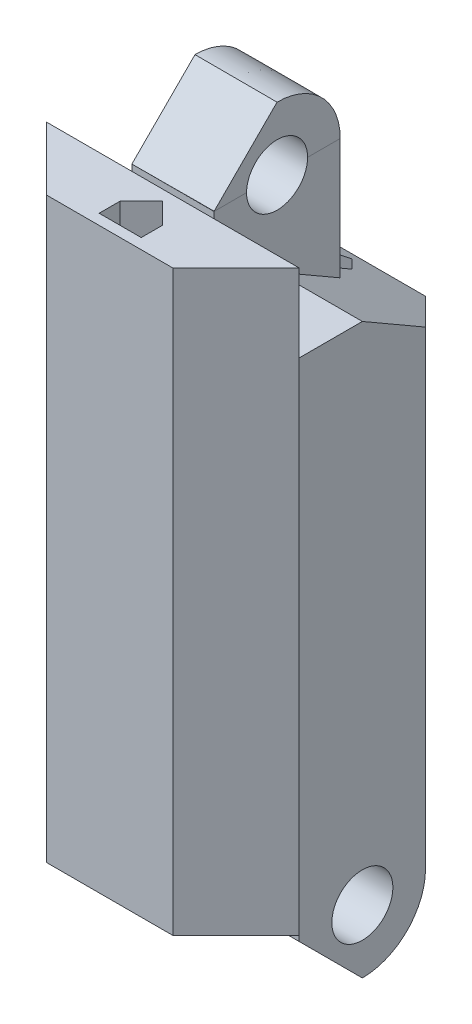
SolidWorks part; units mm, degrees
ref_plane "Front Plane" through (0, 0, 0) normal (0, 0, 1) x (1, 0, 0)
ref_plane "Top Plane" through (0, 0, 0) normal (0, 1, 0) x (1, 0, 0)
ref_plane "Right Plane" through (0, 0, 0) normal (1, 0, 0) x (0, 0, -1)
sketch "Sketch2" plane through (0, 0, 0) normal (0, 1, 0) x (1, 0, 0)
  line L0 (-3, 6) -> (3, 6)
  line L1 (3, 6) -> (6, 3)
  line L2 (6, 3) -> (6, -3)
  line L3 (6, -3) -> (3, -6)
  line L4 (3, -6) -> (-3, -6)
  line L5 (-3, -6) -> (-6, -3)
  line L6 (-6, -3) -> (-6, 3)
  line L7 (-6, 3) -> (-3, 6)
  point P2 (0, -6)
  point P9 (0, 6)
  point P12 (-6, 0)
  point P13 (6, 0)
  dimension "D1" = 12
  dimension "D2" = 12
  dimension "D3" = 6
  dimension "D4" = 6
  dimension "D5" = 6
extrude "Boss-Extrude1" add sketch "Sketch2" along normal mid plane 20 contours L7 L0 L1 L2 L3 L4 L5 L6
sketch "Sketch5" plane through (0, 0, 0) normal (1, 0, 0) x (0, 0, -1)
  line L1 (3, 10) -> (-3, 10) construction
  line L2 (0, 10) -> (6, 6.5359)
  line L3 (6, 10) -> (6, -10) construction
  line L4 (6, 6.5359) -> (6, 10)
  line L5 (6, 10) -> (0, 10)
  dimension "D1" = 30
extrude "Cut-Extrude2" cut sketch "Sketch5" against normal through all both and the other way through all
mirror "Mirror3" about plane through (0, 0, 0) normal (0, 1, 0) of "Cut-Extrude2"
sketch "Sketch6" plane through (0, -10, 0) normal (0, -1, 0) x (1, 0, 0)
  line L1 (-6, 3) -> (-2.1, 3)
  line L2 (-6, 3) -> (-6, -3)
  line L3 (-6, -3) -> (-2.1, -3)
  line L4 (-2.1, 3) -> (-2.1, -3)
  dimension "D1" = 3.9
extrude "Boss-Extrude3" add sketch "Sketch6" along normal mid plane 8
sketch "Sketch7" plane through (0, -14, 0) normal (0, -1, 0) x (1, 0, 0)
  line L0 (-6, 3) -> (-6, -3) construction
  line L1 (-6, 0) -> (-2.1, 0)
  line L2 (-6, 0) -> (-6, 3)
  line L3 (-6, 3) -> (-2.1, 3)
  line L4 (-2.1, 0) -> (-2.1, 3)
revolve "Revolve1" add sketch "Sketch7" angle 180 about L1
sketch "Sketch8" plane through (-6, 0, 0) normal (-1, 0, 0) x (0, 0, 1)
  line L0 (-3, -14) -> (3, -14) construction
sketch "Sketch9" plane through (-6, 0, 0) normal (-1, 0, 0) x (0, 0, 1)
  line L0 (-3, -14) -> (3, -14) construction
  circle A0 centre (0, -14) radius 1.45
  dimension "D1" = 2.9
extrude "Cut-Extrude3" cut sketch "Sketch9" against normal mid plane 10
mirror "Mirror5" about plane through (0, 0, 0) normal (1, 0, 0) of "Revolve1", "Boss-Extrude3", "Cut-Extrude3"
sketch "Sketch10" plane through (0, 10, 0) normal (0, 1, 0) x (1, 0, 0)
  line L0 (-6, -3) -> (6, -3) construction
  line L1 (-1.95, -3) -> (1.95, -3)
  line L2 (-1.95, -3) -> (-1.95, 3)
  line L3 (-1.95, 3) -> (1.95, 3)
  line L4 (1.95, -3) -> (1.95, 3)
  line L5 (-1.95, -3) -> (1.95, 3) construction
  line L6 (-1.95, 3) -> (1.95, -3) construction
  point P6 (0, 0)
  dimension "D1" = 3.9
extrude "Boss-Extrude4" add sketch "Sketch10" along normal mid plane 8
sketch "Sketch12" plane through (0, 14, 0) normal (0, 1, 0) x (1, 0, 0)
  line L0 (-1.95, 3) -> (-1.95, 0)
  line L3 (-1.95, 3) -> (1.95, 3)
  line L4 (1.95, 0.0037) -> (1.95, 3)
  line L5 (-1.95, 3) -> (-1.95, -3) construction
  line L6 (-1.95, 0) -> (1.95, 0.0037)
revolve "Revolve2" add sketch "Sketch12" angle 180 about L6
sketch "Sketch13" plane through (-1.95, 0, 0) normal (-1, 0, 0) x (0, 0, 1)
  line L0 (-3, 14) -> (3, 14) construction
  line L1 (0, 14) -> (3, 14) construction
sketch "Sketch14" plane through (-1.95, 0, 0) normal (-1, 0, 0) x (0, 0, 1)
  line L0 (-3, 14) -> (3, 14) construction
  circle A0 centre (0, 14) radius 1.45
  dimension "D1" = 2.9
extrude "Cut-Extrude4" cut sketch "Sketch14" against normal mid plane 10
sketch "Sketch17" plane through (0, 10, 0) normal (0, 1, 0) x (1, 0, 0)
  line L0 (-6, -3) -> (-1.95, -3)
  line L1 (-1.95, -3) -> (1.95, -3)
  line L2 (6, -3) -> (1.95, -3)
  line L3 (3, -6) -> (6, -3)
  line L4 (-6, -3) -> (-3, -6)
  line L5 (-3, -6) -> (3, -6)
extrude "Boss-Extrude7" add sketch "Sketch17" along normal blind 3.7
sketch "Sketch15" plane through (0, 0, 0) normal (0, 1, 0) x (1, 0, 0)
  line L0 (0, 5.5) -> (-1, 4.5)
  line L1 (-1, 4.5) -> (-1, 3.5)
  line L2 (-1, 3.5) -> (1, 3.5)
  line L3 (1, 3.5) -> (1, 4.5)
  line L4 (1, 4.5) -> (0, 5.5)
  line L6 (1, -4.5) -> (0, -3.5)
  line L7 (0, -3.5) -> (-1, -4.5)
  line L8 (-1, -4.5) -> (-1, -5.5)
  line L9 (-1, -5.5) -> (1, -5.5)
  line L10 (1, -5.5) -> (1, -4.5)
  line L12 (1.95, -3) -> (-1.95, -3) construction
  line L13 (1.95, 3) -> (-1.95, 3) construction
  dimension "D1" = 2
  dimension "D2" = 2
  dimension "D3" = 135
  dimension "D4" = 135
  dimension "D5" = 1
  dimension "D6" = 2
  dimension "D7" = 0.5
  dimension "D8" = 0.5
sketch "Sketch19" plane through (0, -10, 0) normal (0, -1, 0) x (1, 0, 0)
  line L0 (-6, 3) -> (-2.1, 3)
  line L1 (-2.1, 3) -> (2.1, 3)
  line L2 (2.1, 3) -> (6, 3)
  line L3 (6, 3) -> (3, 6)
  line L4 (3, 6) -> (-3, 6)
  line L5 (-3, 6) -> (-6, 3)
extrude "Boss-Extrude17" add sketch "Sketch19" along normal blind 3.75
extrude "Cut-Extrude6" cut sketch "Sketch15" against normal through all both and the other way through all
sketch "Sketch20" plane through (-1.95, 0, 0) normal (-1, 0, 0) x (0, 0, 1)
  line L0 (3, 14) -> (0.0001, 17)
  line L1 (0.0001, 17) -> (0.0001, 17.5375)
  line L2 (0.0001, 17.5375) -> (3, 17.5375)
  line L3 (3, 17.5375) -> (3.3716, 17.5375)
  line L4 (3.3716, 17.5375) -> (3.3716, 14)
  line L5 (3.3716, 14) -> (3, 14)
  ellipse E0 centre (0, 14) end of major axis (0, 11) minor radius 3 (3, 14) -> (-3, 14) ccw construction
extrude "Cut-Extrude7" cut sketch "Sketch20" against normal through all both and the other way through all
sketch "Sketch21" plane through (6, 0, 0) normal (1, 0, 0) x (0, 0, -1)
  line L0 (-3, -14) -> (0, -17)
  line L1 (0, -17) -> (0, -17.7207)
  line L2 (0, -17.7207) -> (-3.5105, -17.7207)
  line L3 (-3.5105, -17.7207) -> (-3.5105, -14.5105)
  line L4 (-3.5105, -14.5105) -> (-3.5105, -14)
  line L5 (-3.5105, -14) -> (-3, -14)
  arc A0 (-3, -14) -> (3, -14) centre (0, -14) ccw construction
extrude "Cut-Extrude8" cut sketch "Sketch21" against normal through all both
